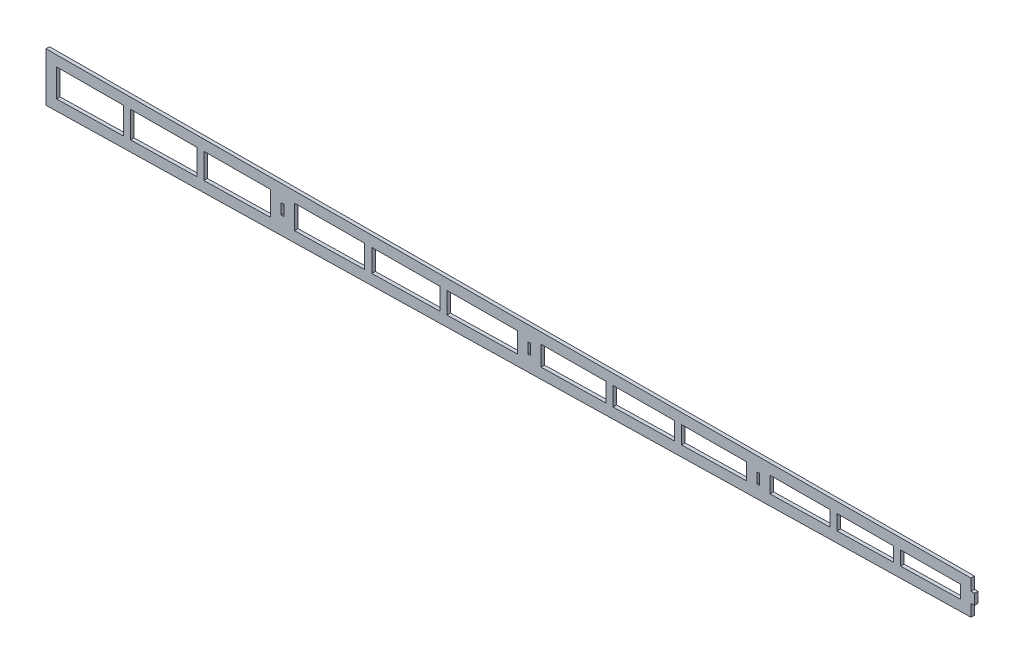
SolidWorks part; units mm, degrees
ref_plane "前视基准面" through (0, 0, 0) normal (0, 0, 1) x (1, 0, 0)
ref_plane "上视基准面" through (0, 0, 0) normal (0, 1, 0) x (1, 0, 0)
ref_plane "右视基准面" through (0, 0, 0) normal (1, 0, 0) x (0, 0, -1)
sketch "草图1" plane through (0, 0, 0) normal (0, 0, 1) x (1, 0, 0)
  line L0 (417.1219, 32.1436) -> (415.6219, 32.1436)
  line L1 (415.6219, 32.1436) -> (415.6219, 26.1436)
  line L2 (415.6219, 26.1436) -> (417.1219, 26.1436)
  line L3 (417.1219, 26.1436) -> (417.1219, 32.1436)
  line L4 (286.8788, 31.0508) -> (285.3788, 31.0508)
  line L5 (285.3788, 31.0508) -> (285.3788, 25.0508)
  line L6 (285.3788, 25.0508) -> (286.8788, 25.0508)
  line L7 (286.8788, 25.0508) -> (286.8788, 31.0508)
  line L8 (146.6171, 29.4156) -> (145.1171, 29.4156)
  line L9 (145.1171, 29.4156) -> (145.1171, 23.4156)
  line L10 (145.1171, 23.4156) -> (146.6171, 23.4156)
  line L11 (146.6171, 23.4156) -> (146.6171, 29.4156)
  line L12 (531.3512, 34.6863) -> (531.3512, 27.2688)
  line L13 (531.3512, 27.2688) -> (497.3519, 26.567)
  line L14 (493.3519, 26.4845) -> (461.1219, 25.8192)
  line L15 (457.1219, 25.7366) -> (423.1219, 25.0348)
  line L16 (423.1219, 25.0348) -> (423.1219, 34.208)
  line L17 (423.1219, 34.208) -> (457.1219, 34.3583)
  line L18 (461.1219, 34.3759) -> (493.3519, 34.5184)
  line L19 (497.3519, 34.5361) -> (531.3512, 34.6863)
  line L20 (409.6219, 34.1483) -> (409.6219, 24.7561)
  line L21 (409.6219, 24.7561) -> (372.7188, 23.9944)
  line L22 (368.7188, 23.9118) -> (333.7788, 23.1906)
  line L23 (329.7788, 23.108) -> (292.8788, 22.3463)
  line L24 (292.8788, 22.3463) -> (292.8788, 33.6324)
  line L25 (292.8788, 33.6324) -> (329.7788, 33.7955)
  line L26 (333.7788, 33.8132) -> (368.7188, 33.9676)
  line L27 (372.7188, 33.9853) -> (409.6219, 34.1483)
  line L28 (279.3788, 33.5727) -> (279.3788, 22.0677)
  line L29 (279.3788, 22.0677) -> (239.3771, 21.242)
  line L30 (235.3771, 21.1594) -> (196.6171, 20.3593)
  line L31 (192.6171, 20.2767) -> (152.6171, 19.4511)
  line L32 (152.6171, 19.4511) -> (152.6171, 33.0125)
  line L33 (152.6171, 33.0125) -> (192.6171, 33.1893)
  line L34 (196.6171, 33.207) -> (235.3771, 33.3783)
  line L35 (239.3771, 33.396) -> (279.3788, 33.5727)
  line L36 (139.1171, 32.9529) -> (139.1171, 19.1724)
  line L37 (139.1171, 19.1724) -> (101.1147, 18.388)
  line L38 (97.1147, 18.3054) -> (59.3647, 17.5262)
  line L39 (55.3647, 17.4436) -> (17.3647, 16.6592)
  line L40 (17.3647, 16.6592) -> (17.3647, 32.4148)
  line L41 (17.3647, 32.4148) -> (55.3647, 32.5827)
  line L42 (59.3647, 32.6004) -> (97.1147, 32.7672)
  line L43 (101.1147, 32.7849) -> (139.1171, 32.9529)
  line L44 (497.3519, 34.5361) -> (497.3519, 26.567)
  line L45 (493.3519, 34.5184) -> (493.3519, 26.4845)
  line L46 (461.1219, 34.3759) -> (461.1219, 25.8192)
  line L47 (457.1219, 34.3583) -> (457.1219, 25.7366)
  line L48 (372.7188, 33.9853) -> (372.7188, 23.9944)
  line L49 (368.7188, 33.9676) -> (368.7188, 23.9118)
  line L50 (333.7788, 33.8132) -> (333.7788, 23.1906)
  line L51 (329.7788, 33.7955) -> (329.7788, 23.108)
  line L52 (239.3771, 33.396) -> (239.3771, 21.242)
  line L53 (235.3771, 33.3783) -> (235.3771, 21.1594)
  line L54 (196.6171, 33.207) -> (196.6171, 20.3593)
  line L55 (192.6171, 33.1893) -> (192.6171, 20.2767)
  line L56 (101.1147, 32.7849) -> (101.1147, 18.388)
  line L57 (97.1147, 32.7672) -> (97.1147, 18.3054)
  line L58 (59.3647, 32.6004) -> (59.3647, 17.5262)
  line L59 (55.3647, 32.5827) -> (55.3647, 17.4436)
  line L60 (537.3512, 34.1942) -> (539.3512, 34.1942)
  line L61 (539.3512, 34.1942) -> (539.3512, 28.1942)
  line L62 (539.3512, 28.1942) -> (537.3512, 28.1942)
  line L63 (537.3512, 28.1942) -> (537.3512, 21.3914)
  line L64 (537.3512, 21.3914) -> (11.3647, 10.5341)
  line L65 (11.3647, 10.5341) -> (11.3647, 38.3883)
  line L66 (11.3647, 38.3883) -> (537.3512, 40.7129)
  line L67 (537.3512, 40.7129) -> (537.3512, 34.1942)
extrude "凸台-拉伸1" add sketch "草图1" along normal blind 2
